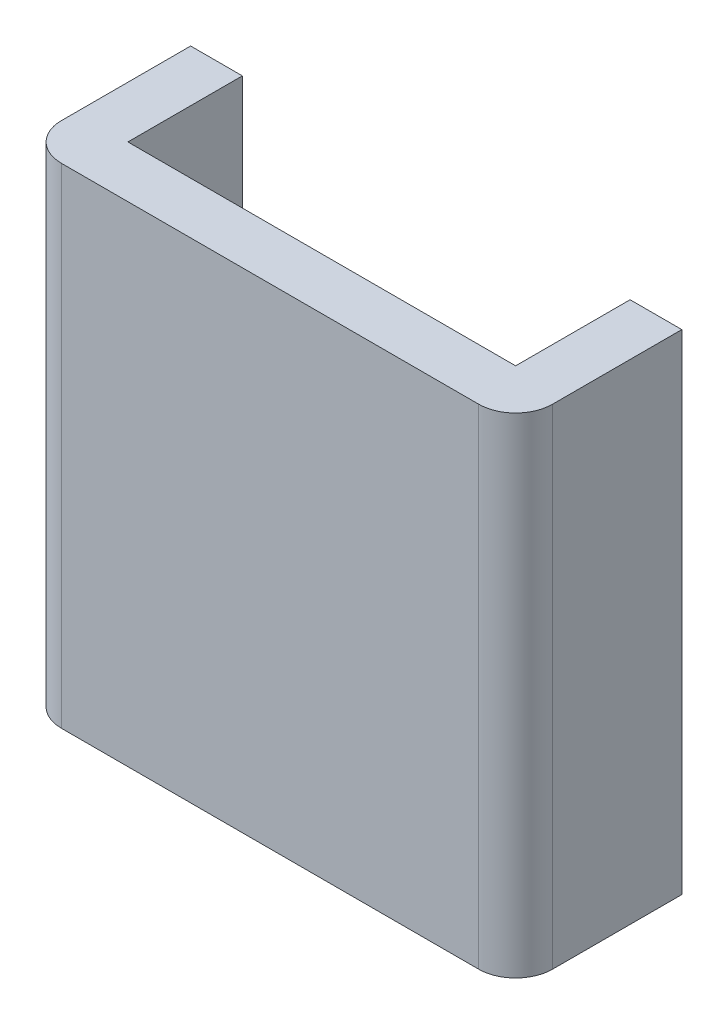
SolidWorks part; units mm, degrees
ref_plane "Plan de face" through (0, 0, 0) normal (0, 0, 1) x (1, 0, 0)
ref_plane "Plan de dessus" through (0, 0, 0) normal (0, 1, 0) x (1, 0, 0)
ref_plane "Plan de droite" through (0, 0, 0) normal (1, 0, 0) x (0, 0, -1)
sketch "Esquisse1" plane through (0, 0, 0) normal (0, 1, 0) x (1, 0, 0)
  line L0 (-13.3, 0) -> (13.3, 0)
  line L1 (13.3, 0) -> (13.3, 9)
  line L2 (13.3, 9) -> (10.5, 9)
  line L3 (10.5, 9) -> (10.5, 2.8)
  line L4 (10.5, 2.8) -> (-10.5, 2.8)
  line L5 (-10.5, 2.8) -> (-10.5, 9)
  line L6 (-10.5, 9) -> (-13.3, 9)
  line L7 (-13.3, 9) -> (-13.3, 0)
  point P4 (0, 0)
  dimension "D1" = 21
  dimension "D2" = 2.8
  dimension "D3" = 2.8
  dimension "D4" = 6.2
extrude "Boss.-Extru.1" add sketch "Esquisse1" along normal blind 26.5
fillet "Congé1" radius 2 2 edges at (13.3, 13.25, 0) (-13.3, 13.25, 0)
